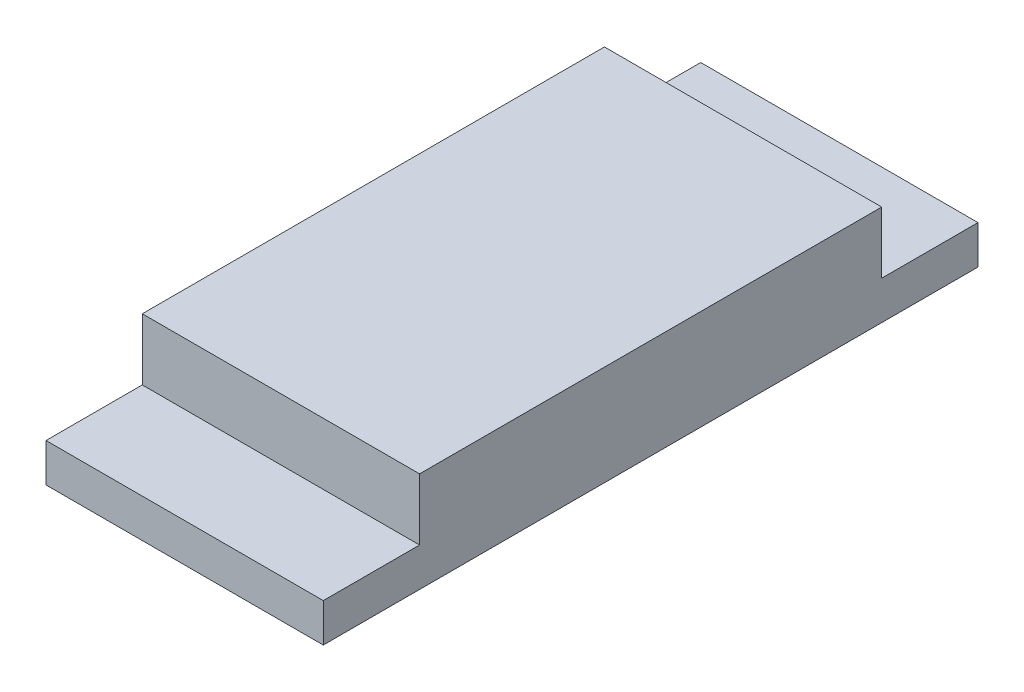
SolidWorks part; units mm, degrees
ref_plane "Front Plane" through (0, 0, 0) normal (0, 0, 1) x (1, 0, 0)
ref_plane "Top Plane" through (0, 0, 0) normal (0, 1, 0) x (1, 0, 0)
ref_plane "Right Plane" through (0, 0, 0) normal (1, 0, 0) x (0, 0, -1)
sketch "Sketch1" plane through (0, 0, 0) normal (1, 0, 0) x (0, 0, -1)
  line L0 (0, 0) -> (85, 0)
  line L1 (85, 0) -> (85, 5)
  line L2 (85, 5) -> (72.5, 5)
  line L3 (72.5, 5) -> (72.5, 13)
  line L4 (72.5, 13) -> (12.5, 13)
  line L5 (12.5, 13) -> (12.5, 5)
  line L6 (12.5, 5) -> (0, 5)
  line L7 (0, 5) -> (0, 0)
  dimension "D1" = 85
  dimension "D2" = 13
  dimension "D3" = 5
  dimension "D4" = 60
  dimension "D5" = 12.5
  dimension "D6" = 12.5
extrude "Boss-Extrude1" add sketch "Sketch1" along normal blind 36
